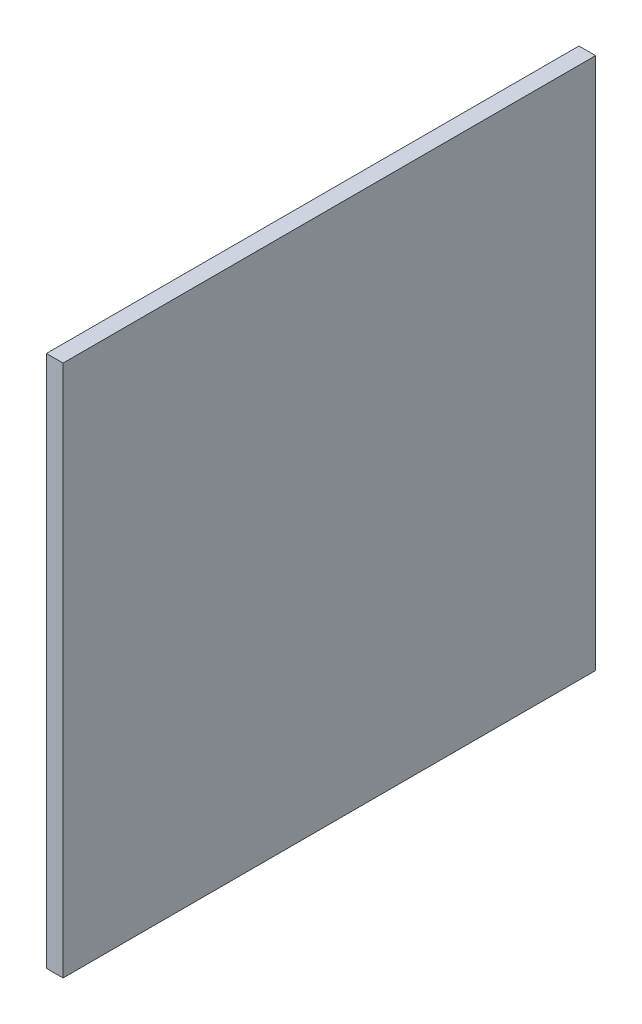
SolidWorks part; units mm, degrees
ref_plane "Front Plane" through (0, 0, 0) normal (0, 0, 1) x (1, 0, 0)
ref_plane "Top Plane" through (0, 0, 0) normal (0, 1, 0) x (1, 0, 0)
ref_plane "Right Plane" through (0, 0, 0) normal (1, 0, 0) x (0, 0, -1)
sketch "Sketch1" plane through (0, 0, 0) normal (1, 0, 0) x (0, 0, -1)
  line L1 (-101.6, -101.6) -> (101.6, -101.6)
  line L2 (-101.6, -101.6) -> (-101.6, 101.6)
  line L3 (-101.6, 101.6) -> (101.6, 101.6)
  line L4 (101.6, -101.6) -> (101.6, 101.6)
  line L5 (-101.6, -101.6) -> (101.6, 101.6) construction
  line L6 (-101.6, 101.6) -> (101.6, -101.6) construction
  point P0 (0, 0)
  dimension "D1" = 203.2
  dimension "D2" = 203.2
extrude "Boss-Extrude1" add sketch "Sketch1" along normal blind 6.35
sketch "Sketch3" plane through (6.35, 0, 0) normal (1, 0, 0) x (0, 0, -1)
  line L0 (0, 101.6) -> (0, -101.6) construction
  line L1 (101.6, 101.6) -> (-101.6, 101.6) construction
  line L2 (-101.6, -101.6) -> (101.6, -101.6) construction
  line L3 (-101.6, 12.7) -> (101.6, 12.7) construction
  line L6 (-101.6, 101.6) -> (-101.6, -101.6) construction
  line L7 (101.6, -101.6) -> (101.6, 101.6) construction
  point P12 (0, 12.7)
  point P13 (0, 7.6873)
  dimension "D1" = 12.7
